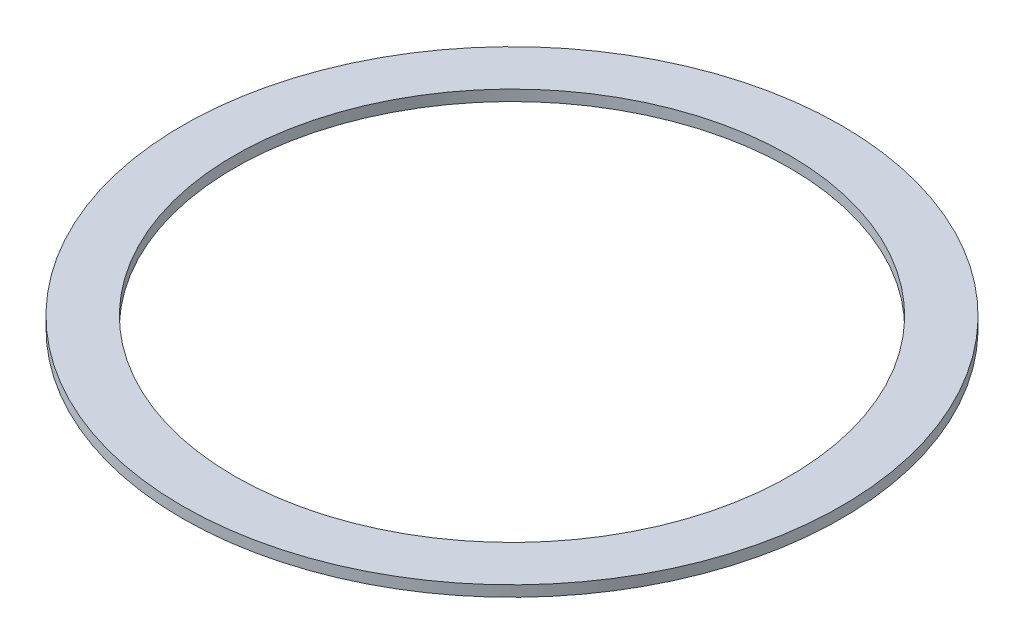
SolidWorks part; units mm, degrees
ref_plane "Front Plane" through (0, 0, 0) normal (0, 0, 1) x (1, 0, 0)
ref_plane "Top Plane" through (0, 0, 0) normal (0, 1, 0) x (1, 0, 0)
ref_plane "Right Plane" through (0, 0, 0) normal (1, 0, 0) x (0, 0, -1)
sketch "Sketch1" plane through (0, 0, 0) normal (0, 1, 0) x (1, 0, 0)
  circle A0 centre (0, 0) radius 76.2
  circle A1 centre (0, 0) radius 64.2
  dimension "D1" = 152.4
  dimension "D2" = 12
extrude "Boss-Extrude1" add sketch "Sketch1" along normal blind 2.5
